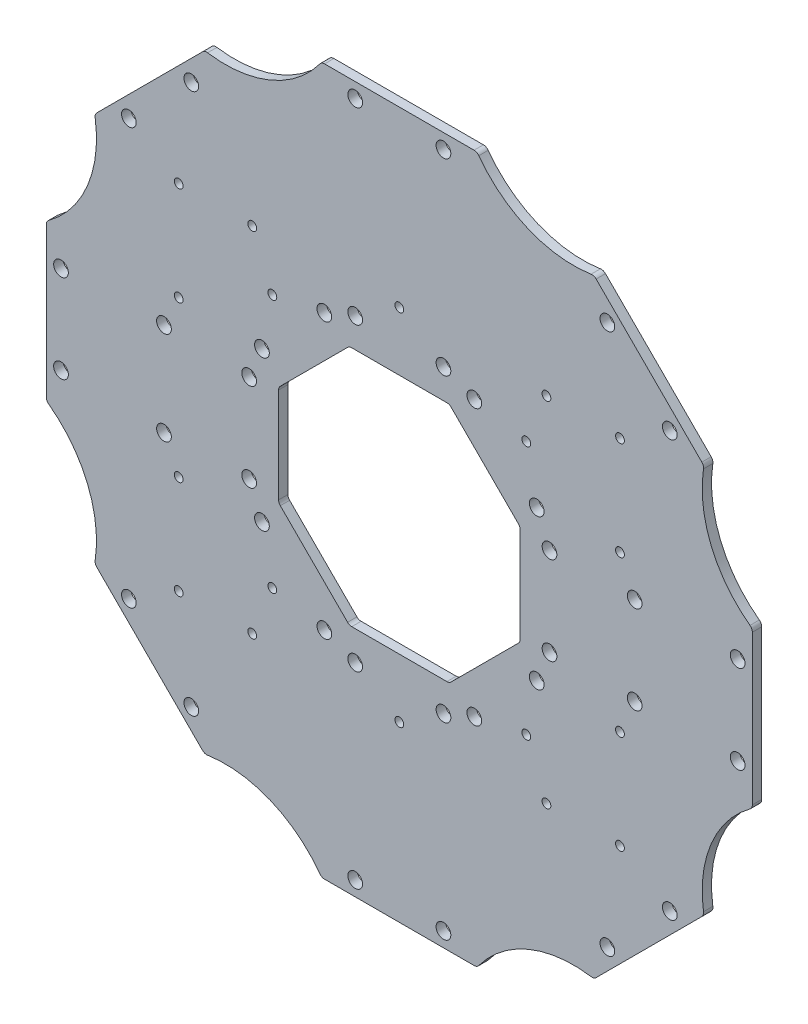
SolidWorks part; units mm, degrees
ref_plane "Front Plane" through (0, 0, 0) normal (0, 0, 1) x (1, 0, 0)
ref_plane "Top Plane" through (0, 0, 0) normal (0, 1, 0) x (1, 0, 0)
ref_plane "Right Plane" through (0, 0, 0) normal (1, 0, 0) x (0, 0, -1)
sketch "Sketch1" plane through (0, 0, 0) normal (0, 0, 1) x (1, 0, 0)
  line L0 (-120, 0) -> (-80, 0) construction
  line L1 (80, 0) -> (120, 0) construction
  line L2 (-15, 115) -> (15, 115) construction
  line L3 (-41.0416, 17) -> (-17, 41.0416)
  line L4 (80, 15) -> (80, -15) construction
  line L5 (-80, 15.8492) -> (-80, -15.8492) construction
  line L6 (-120, 26.4332) -> (-120, -26.4332)
  line L9 (-26.4332, 120) -> (26.4332, 120)
  line L11 (-51.0416, 0) -> (-41.0416, 0) construction
  line L12 (-103.5449, 66.1651) -> (-66.1651, 103.5449)
  line L13 (0, 59.5416) -> (0, 41.0416) construction
  line L14 (0, 59.5416) -> (0, -59.5416) construction
  line L16 (-120, 26.4332) -> (-75, 26.4332) construction
  line L17 (0, 120) -> (0, 135) construction
  line L19 (-41.0416, 17) -> (-41.0416, -17)
  line L20 (-17, 41.0416) -> (17, 41.0416)
  line L21 (75, 60) -> (75, -60) construction
  line L22 (51.0416, 0) -> (41.0416, 0) construction
  line L23 (-41.0416, 0) -> (41.0416, 0) construction
  line L24 (0, 41.0416) -> (0, -41.0416) construction
  line L25 (51.0416, 15) -> (51.0416, -15) construction
  line L28 (41.0416, 17) -> (41.0416, -17)
  line L29 (103.5449, 66.1651) -> (66.1651, 103.5449)
  line L30 (120, 26.4332) -> (120, -26.4332)
  line L31 (41.0416, 17) -> (17, 41.0416)
  line L32 (75, -60) -> (50, -60) construction
  line L35 (-120, -26.4332) -> (-75, -26.4332) construction
  line L36 (0, -59.5416) -> (0, -41.0416) construction
  line L38 (0, -51.0416) -> (0, -41.0416) construction
  line L39 (-15, -115) -> (15, -115) construction
  line L41 (0, -120) -> (0, -62.5416) construction
  line L42 (41.0416, -17) -> (17, -41.0416)
  line L43 (103.5449, -66.1651) -> (66.1651, -103.5449)
  line L44 (-17, -41.0416) -> (17, -41.0416)
  line L45 (-103.5449, -66.1651) -> (-66.1651, -103.5449)
  line L46 (-26.4332, -120) -> (26.4332, -120)
  line L47 (-41.0416, -17) -> (-17, -41.0416)
  circle A0 centre (-91.9261, 70.7129) radius 2.5
  circle A1 centre (-70.7129, 91.9261) radius 2.5
  circle A2 centre (-25.4853, 46.6985) radius 2.5
  circle A3 centre (-46.6985, 25.4853) radius 2.5
  circle A4 centre (-15, 115) radius 2.5
  circle A5 centre (-15, 51.0416) radius 2.5
  circle A6 centre (-115, 15) radius 2.5
  circle A7 centre (-51.0416, 15) radius 2.5
  arc A8 (-120, 26.4332) -> (-103.5449, 66.1651) centre (-142.9347, 59.2051) ccw
  arc A9 (-66.1651, 103.5449) -> (-26.4332, 120) centre (-59.2051, 142.9347) ccw
  circle A10 centre (-75, 60) radius 1.5
  circle A11 centre (-50, 60) radius 1.5
  circle A12 centre (-43.163, 43.163) radius 1.5
  circle A13 centre (0, 61.0416) radius 1.5
  circle A14 centre (-75, 26.4332) radius 1.5
  circle A15 centre (75, 26.4332) radius 1.5
  circle A16 centre (43.163, 43.163) radius 1.5
  circle A17 centre (50, 60) radius 1.5
  circle A18 centre (75, 60) radius 1.5
  arc A19 (66.1651, 103.5449) -> (26.4332, 120) centre (59.2051, 142.9347) cw
  arc A20 (120, 26.4332) -> (103.5449, 66.1651) centre (142.9347, 59.2051) cw
  circle A21 centre (51.0416, 15) radius 2.5
  circle A22 centre (115, 15) radius 2.5
  circle A23 centre (15, 51.0416) radius 2.5
  circle A24 centre (15, 115) radius 2.5
  circle A25 centre (46.6985, 25.4853) radius 2.5
  circle A26 centre (25.4853, 46.6985) radius 2.5
  circle A27 centre (70.7129, 91.9261) radius 2.5
  circle A28 centre (91.9261, 70.7129) radius 2.5
  circle A29 centre (91.9261, -70.7129) radius 2.5
  circle A30 centre (70.7129, -91.9261) radius 2.5
  circle A31 centre (25.4853, -46.6985) radius 2.5
  circle A32 centre (46.6985, -25.4853) radius 2.5
  circle A33 centre (15, -115) radius 2.5
  circle A34 centre (15, -51.0416) radius 2.5
  circle A35 centre (115, -15) radius 2.5
  circle A36 centre (51.0416, -15) radius 2.5
  arc A37 (120, -26.4332) -> (103.5449, -66.1651) centre (142.9347, -59.2051) ccw
  arc A38 (66.1651, -103.5449) -> (26.4332, -120) centre (59.2051, -142.9347) ccw
  circle A39 centre (75, -60) radius 1.5
  circle A40 centre (50, -60) radius 1.5
  circle A41 centre (43.163, -43.163) radius 1.5
  circle A42 centre (75, -26.4332) radius 1.5
  circle A43 centre (-75, -26.4332) radius 1.5
  circle A44 centre (0, -61.0416) radius 1.5
  circle A45 centre (-43.163, -43.163) radius 1.5
  circle A46 centre (-50, -60) radius 1.5
  circle A47 centre (-75, -60) radius 1.5
  arc A48 (-66.1651, -103.5449) -> (-26.4332, -120) centre (-59.2051, -142.9347) cw
  arc A49 (-120, -26.4332) -> (-103.5449, -66.1651) centre (-142.9347, -59.2051) cw
  circle A50 centre (-51.0416, -15) radius 2.5
  circle A51 centre (-115, -15) radius 2.5
  circle A52 centre (-15, -51.0416) radius 2.5
  circle A53 centre (-15, -115) radius 2.5
  circle A54 centre (-46.6985, -25.4853) radius 2.5
  circle A55 centre (-25.4853, -46.6985) radius 2.5
  circle A56 centre (-70.7129, -91.9261) radius 2.5
  circle A57 centre (-91.9261, -70.7129) radius 2.5
  circle A58 centre (-80, 15.8492) radius 2.5
  circle A59 centre (-80, -15.8492) radius 2.5
  circle A60 centre (80, -15) radius 2.5
  circle A61 centre (80, 15) radius 2.5
  point P2 (0, 0)
  point P55 (-80, 0)
  point P92 (80, 0)
  point P158 (0, 0)
  point P162 (-120, 0)
  point P163 (120, 0)
  dimension "D19" = 5
  dimension "D15" = 5
  dimension "D20" = 46.6985
  dimension "D8" = 5
  dimension "D3" = 5
  dimension "D21" = 70.7129
  dimension "D7" = 5
  dimension "D4" = 40
  dimension "D9" = 30
  dimension "D23" = 91.9261
extrude "Boss-Extrude2" add sketch "Sketch1" along normal blind 3.175
fillet "Fillet2" radius 2 24 edges at (-41.0416, 17, 1.5875) (-17, 41.0416, 1.5875) (17, 41.0416, 1.5875) (41.0416, 17, 1.5875) (41.0416, -17, 1.5875) (17, -41.0416, 1.5875) (-41.0416, -17, 1.5875) (-17, -41.0416, 1.5875) (26.4332, 120, 1.5875) (-26.4332, 120, 1.5875) (-66.1651, 103.5449, 1.5875) (-103.5449, 66.1651, 1.5875) (-120, 26.4332, 1.5875) (-120, -26.4332, 1.5875) (-103.5449, -66.1651, 1.5875) (-66.1651, -103.5449, 1.5875) (-26.4332, -120, 1.5875) (26.4332, -120, 1.5875) (66.1651, -103.5449, 1.5875) (103.5449, -66.1651, 1.5875) (120, -26.4332, 1.5875) (120, 26.4332, 1.5875) (103.5449, 66.1651, 1.5875) (66.1651, 103.5449, 1.5875)
